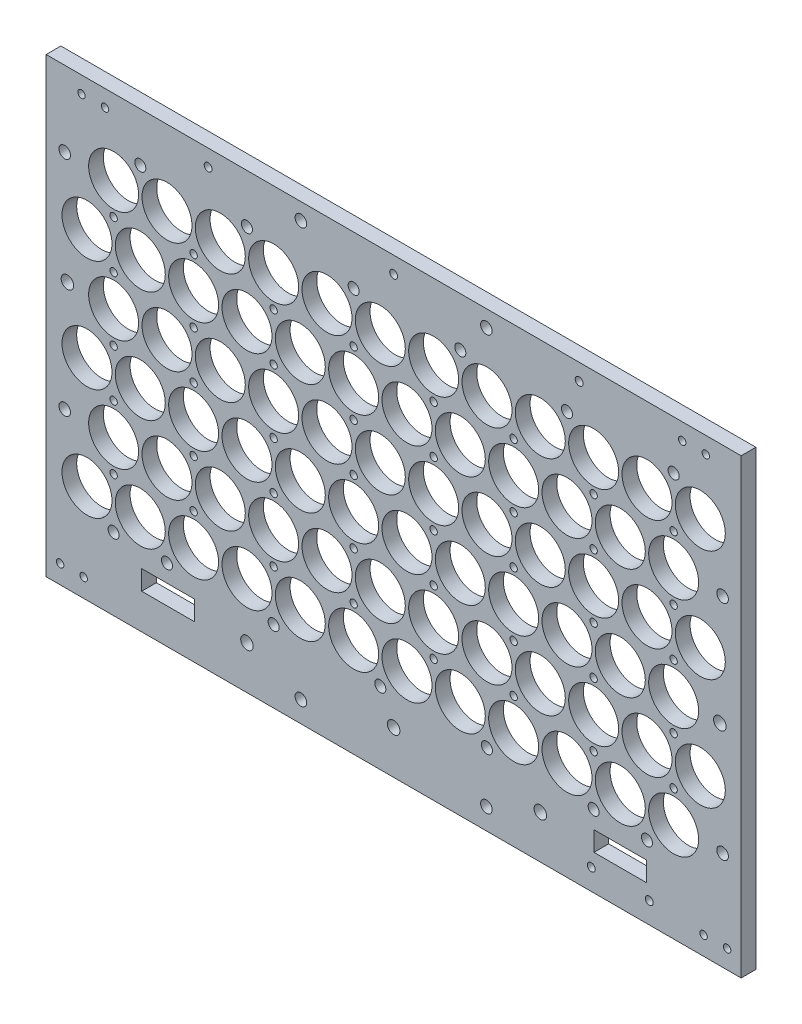
SolidWorks part; units mm, degrees
material "ABS"
ref_plane "X-Y Datum" through (0, 0, 0) normal (0, 0, 1) x (1, 0, 0)
ref_plane "X-Z Datum" through (0, 0, 0) normal (0, 1, 0) x (1, 0, 0)
ref_plane "Y-Z Datum" through (0, 0, 0) normal (1, 0, 0) x (0, 0, -1)
sketch "Sketch1" plane through (0, 0, 0) normal (0, 0, 1) x (1, 0, 0)
  line L1 (-143.025, 70.775) -> (143.025, 70.775)
  line L2 (-143.025, 70.775) -> (-143.025, -70.775)
  line L3 (-143.025, -70.775) -> (143.025, -70.775)
  line L4 (143.025, 70.775) -> (143.025, -70.775)
  line L5 (-143.025, 70.775) -> (143.025, -70.775) construction
  line L6 (-143.025, -70.775) -> (143.025, 70.775) construction
  line L13 (-149.85, -102.6) -> (149.85, -102.6)
  line L14 (-149.85, 91.65) -> (149.85, 91.65)
  line L15 (-149.85, 91.65) -> (-149.85, -102.6)
  line L16 (149.85, 91.65) -> (149.85, -102.6)
  line L17 (149.85, 70.775) -> (149.85, -70.775) construction
  line L18 (-143.025, 91.65) -> (143.025, 91.65) construction
  line L19 (-143.025, -102.6) -> (143.025, -102.6) construction
  line L20 (-149.85, 70.775) -> (-149.85, -70.775) construction
  line L21 (-132.25, -60) -> (-109.25, -60) construction
  circle A0 centre (-132.25, -60) radius 10.775
  circle A1 centre (-109.25, -60) radius 10.775 construction
  circle A2 centre (-120.75, -36) radius 10.775
  point P0 (0, 0)
  point P16 (-120.75, -60)
  dimension "D1" = 21.55
  dimension "D2" = 23
  dimension "D3" = 24
  dimension "D5" = 141.55
  dimension "D6" = 286.05
  dimension "D7" = 31.825
  dimension "D8" = 20.875
  dimension "D9" = 6.825
  dimension "D10" = 6.825
extrude "Boss-Extrude1" add sketch "Sketch1" along normal blind 6.35
sketch "Sketch3" plane through (0, 0, 6.35) normal (0, 0, 1) x (1, 0, 0)
  line L4 (143.025, 70.775) -> (-143.025, 70.775)
  line L5 (143.025, -70.775) -> (143.025, 70.775)
  line L6 (-143.025, -70.775) -> (143.025, -70.775)
  line L7 (-143.025, 70.775) -> (-143.025, -70.775)
  line L8 (143.025, 70.775) -> (-143.025, 70.775)
  line L9 (143.025, -70.775) -> (143.025, 70.775)
  line L10 (-143.025, -70.775) -> (143.025, -70.775)
  line L11 (-143.025, 70.775) -> (-143.025, -70.775)
  circle A1 centre (-120.75, -36) radius 10.775
  circle A2 centre (-120.75, -36) radius 10.775
  circle A3 centre (-132.25, -60) radius 10.775
  circle A4 centre (-132.25, -60) radius 10.775
  dimension "D1" = 0
  dimension "D2" = 0
  dimension "D3" = 0
extrude "Cut-Extrude1" cut sketch "Sketch3" against normal through all contours A4
sketch "Sketch4" plane through (0, 0, 6.35) normal (0, 0, 1) x (1, 0, 0)
  line L4 (143.025, 70.775) -> (-143.025, 70.775)
  line L5 (143.025, -70.775) -> (143.025, 70.775)
  line L6 (-143.025, -70.775) -> (143.025, -70.775)
  line L7 (-143.025, 70.775) -> (-143.025, -70.775)
  line L8 (143.025, 70.775) -> (-143.025, 70.775)
  line L9 (143.025, -70.775) -> (143.025, 70.775)
  line L10 (-143.025, -70.775) -> (143.025, -70.775)
  line L11 (-143.025, 70.775) -> (-143.025, -70.775)
  circle A1 centre (-120.75, -36) radius 10.775
  circle A2 centre (-120.75, -36) radius 10.775
  circle A3 centre (-132.25, -60) radius 10.775
  circle A4 centre (-132.25, -60) radius 10.775
  dimension "D1" = 0
  dimension "D2" = 0
  dimension "D3" = 0
extrude "Cut-Extrude2" cut sketch "Sketch4" against normal through all contours A2
pattern_linear "LPattern1" count 12 spacing 23 along (1, 0, 0) of "Cut-Extrude1", "Cut-Extrude2"
pattern_linear "LPattern2" count 3 spacing 48 along (0, 1, 0) of "LPattern1", "Cut-Extrude1", "Cut-Extrude2"
sketch "Sketch5" plane through (0, 0, 6.35) normal (0, 0, 1) x (1, 0, 0)
  line L4 (105.3154, -79.3475) -> (90.1846, -79.3475)
  line L5 (90.37, -80.3) -> (90.37, -83.4115)
  line L6 (90.37, -83.4115) -> (105.13, -83.4115)
  line L7 (105.13, -83.4115) -> (105.13, -80.3)
  line L8 (105.3154, -79.3475) -> (90.1846, -79.3475)
  line L9 (90.37, -80.3) -> (90.37, -83.4115)
  line L10 (90.37, -83.4115) -> (105.13, -83.4115)
  line L11 (105.13, -83.4115) -> (105.13, -80.3)
  line L12 (-108.668, -78.95) -> (-108.668, -87.4115)
  line L13 (-108.668, -87.4115) -> (-85.908, -87.4115)
  line L14 (-85.908, -87.4115) -> (-85.908, -78.95)
  line L15 (86.37, -78.95) -> (86.37, -87.4115)
  line L16 (-89.7226, -79.3475) -> (-104.8534, -79.3475)
  line L17 (-104.668, -80.3) -> (-104.668, -83.4115)
  line L18 (-104.668, -83.4115) -> (-89.908, -83.4115)
  line L19 (-89.908, -83.4115) -> (-89.908, -80.3)
  line L20 (-89.7226, -79.3475) -> (-104.8534, -79.3475)
  line L21 (-104.668, -80.3) -> (-104.668, -83.4115)
  line L22 (-104.668, -83.4115) -> (-89.908, -83.4115)
  line L23 (-89.908, -83.4115) -> (-89.908, -80.3)
  line L24 (86.37, -87.4115) -> (109.13, -87.4115)
  line L25 (109.13, -87.4115) -> (109.13, -78.95)
  line L26 (149.85, -78.95) -> (-149.85, -78.95) construction
  line L27 (149.85, -78.95) -> (-149.85, -78.95)
  line L28 (109.13, -87.4115) -> (109.13, -80.3) construction
  line L29 (86.37, -80.3) -> (86.37, -87.4115) construction
  line L30 (-85.908, -87.4115) -> (-85.908, -80.3) construction
  line L31 (-108.668, -80.3) -> (-108.668, -87.4115) construction
  arc A2 (90.37, -80.3) -> (90.1846, -79.3475) centre (87.83, -80.3) ccw
  arc A3 (105.3154, -79.3475) -> (105.13, -80.3) centre (107.67, -80.3) ccw
  arc A4 (90.37, -80.3) -> (90.1846, -79.3475) centre (87.83, -80.3) ccw
  arc A5 (105.3154, -79.3475) -> (105.13, -80.3) centre (107.67, -80.3) ccw
  arc A8 (-104.668, -80.3) -> (-104.8534, -79.3475) centre (-107.208, -80.3) ccw
  arc A9 (-89.7226, -79.3475) -> (-89.908, -80.3) centre (-87.368, -80.3) ccw
  arc A10 (-104.668, -80.3) -> (-104.8534, -79.3475) centre (-107.208, -80.3) ccw
  arc A11 (-89.7226, -79.3475) -> (-89.908, -80.3) centre (-87.368, -80.3) ccw
  dimension "D1" = 0
  dimension "D2" = 0
  dimension "D3" = 4
extrude "Cut-Extrude3" cut sketch "Sketch5" against normal through all contours L25 L27 L15 L24 L8 A5 L11 L10 L9 A4 | A5 L8 A4 L9 L10 L11 | L14 L27 L12 L13 L20 A11 L23 L22 L21 A10 | A11 L20 A10 L21 L22 L23
sketch "Sketch7" plane through (0, 0, 6.35) normal (0, 0, 1) x (1, 0, 0)
  point P0 (0, 85.3)
  point P1 (80, 85.3)
  point P3 (-124.45, 85.3)
  point P5 (-134.61, 85.3)
  point P7 (-133.6575, -94.6)
  point P9 (-143.8175, -94.6)
  point P11 (133.6575, -94.6)
  point P13 (143.8175, -94.6)
  point P17 (124.45, 85.3)
  point P19 (134.61, 85.3)
  point P21 (110.25, -93.5057)
  point P23 (85.25, -93.5057)
  point P28 (-80, 85.3)
hole_wizard "M3 Clearance Hole1" positions "Sketch8" profile "Sketch9" hole size "M3" standard "ANSI Metric" end condition through all
sketch "Sketch8" plane through (0, 0, 6.35) normal (0, 0, 1) x (1, 0, 0)
  point P3 (124.45, 85.3)
  point P6 (134.61, 85.3)
  point P12 (-124.45, 85.3)
  point P15 (-134.61, 85.3)
  point P18 (-143.8175, -94.6)
  point P21 (-133.6575, -94.6)
  point P24 (133.6575, -94.6)
  point P27 (143.8175, -94.6)
sketch "Sketch9" plane through (124.45, 85.3, 6.35) normal (1, 0, 0) x (0, -1, 0)
  line L0 (0, 0) -> (0, 6.35)
  line L1 (0, 6.35) -> (1.6, 6.35)
  line L2 (1.6, 6.35) -> (1.6, 0)
  line L5 (1.6, 0) -> (0, 0)
  line L11 (0, -6.35) -> (0, 107.95) construction
  dimension "Thru Hole Dia." = 3.2
  dimension "Thru Hole Depth" = 6.35
hole_wizard "M3 Clearance Hole2" positions "Sketch20" profile "Sketch13" hole size "M3" standard "ANSI Metric" end condition through all
sketch "Sketch20" plane through (0, 0, 6.35) normal (0, 0, 1) x (1, 0, 0)
  point P0 (110.25, -93.5057)
  point P3 (85.25, -93.5057)
  point P6 (-80, 85.3)
  point P9 (0, 85.3)
  point P12 (80, 85.3)
  point P23 (0, 0)
  point P24 (0, 0)
sketch "Sketch13" plane through (110.25, -93.5057, 6.35) normal (1, 0, 0) x (0, -1, 0)
  line L0 (0, 0) -> (0, 6.35)
  line L1 (0, 6.35) -> (1.7, 6.35)
  line L2 (1.7, 6.35) -> (1.7, 0)
  line L5 (1.7, 0) -> (0, 0)
  line L11 (0, -6.35) -> (0, 107.95) construction
  dimension "Thru Hole Dia." = 3.4
  dimension "Thru Hole Depth" = 6.35
sketch "Sketch14" plane through (0, 0, 6.35) normal (0, 0, 1) x (1, 0, 0)
  line L0 (131.525, -12) -> (149.85, -12) construction
  line L1 (149.85, 91.65) -> (149.85, -102.6) construction
  line L2 (-131.525, 12) -> (-149.85, 12) construction
  line L3 (-149.85, 91.65) -> (-149.85, -102.6) construction
  line L4 (149.85, -78.95) -> (-149.85, -78.95) construction
  line L5 (149.85, -78.95) -> (-149.85, -78.95) construction
  line L6 (149.85, -83.95) -> (-149.85, -83.95) construction
  line L7 (68.55, -70.9014) -> (57.95, -70.9014) construction
  line L8 (68.55, -67.0427) -> (68.55, -74.76) construction
  line L9 (57.95, -67.0427) -> (57.95, -74.76) construction
  line L10 (63.25, -70.9014) -> (63.25, -83.95) construction
  line L18 (0, -3.4925) -> (0, 3.4925) construction
  circle A0 centre (120.75, -12) radius 10.775 construction
  circle A1 centre (-120.75, 12) radius 10.775 construction
  circle A2 centre (140.6875, -12) radius 2.7
  circle A3 centre (-140.6875, 12) radius 2.7
  circle A4 centre (63.25, -83.95) radius 2.7
  circle A6 centre (-63.25, -83.95) radius 2.7
  circle A8 centre (0, -83.95) radius 2.7
  dimension "D1" = 5.4
  dimension "D3" = 5.4
  dimension "D2" = 5
extrude "Cut-Extrude4" cut sketch "Sketch14" against normal through all
sketch "Sketch15" plane through (0, 0, 6.35) normal (0, 0, 1) x (1, 0, 0)
  line L0 (-6.35, 85.3) -> (86.35, 85.3) construction
  line L1 (-6.35, 90.65) -> (-6.35, 79.95) construction
  line L2 (86.35, 79.95) -> (86.35, 90.65) construction
  line L3 (-86.35, 85.3) -> (6.35, 85.3) construction
  line L4 (-86.35, 90.65) -> (-86.35, 79.95) construction
  line L5 (6.35, 79.95) -> (6.35, 90.65) construction
  line L6 (131.525, 36) -> (149.85, 36) construction
  line L7 (149.85, 94.825) -> (149.85, -105.775) construction
  line L8 (131.525, -60) -> (149.85, -60) construction
  line L9 (-131.525, -36) -> (-149.85, -36) construction
  line L10 (-149.85, -105.775) -> (-149.85, 94.825) construction
  line L11 (-131.525, 60) -> (-149.85, 60) construction
  line L12 (-40, 85.3) -> (-40, -102.6) construction
  line L13 (-149.85, -102.6) -> (149.85, -102.6) construction
  line L14 (40, 85.3) -> (40, -102.6) construction
  line L16 (85.25, -93.5057) -> (-85.25, -93.5057) construction
  circle A0 centre (-40, 85.3) radius 2.5
  circle A1 centre (40, 85.3) radius 2.5
  circle A2 centre (120.75, 36) radius 10.775 construction
  circle A3 centre (120.75, -60) radius 10.775 construction
  circle A4 centre (141.85, 36) radius 2.5
  circle A5 centre (141.85, -60) radius 2.5
  circle A6 centre (-120.75, -36) radius 10.775 construction
  circle A7 centre (-120.75, 60) radius 10.775 construction
  circle A8 centre (-141.85, -36) radius 2.5
  circle A9 centre (-141.85, 60) radius 2.5
  circle A10 centre (-40, -93.5057) radius 2.5
  circle A11 centre (40, -93.5057) radius 2.5
  dimension "D1" = 5
  dimension "D2" = 8
  dimension "D3" = 8
  dimension "D4" = 8
  dimension "D5" = 8
extrude "Cut-Extrude5" cut sketch "Sketch15" against normal through all
sketch "Sketch16" plane through (0, 0, 6.35) normal (0, 0, 1) x (1, 0, 0)
  circle A0 centre (86.25, 46.29) radius 1.1906 construction
  circle A1 centre (120.75, 49.71) radius 1.1906 construction
  circle A2 centre (86.25, 25.71) radius 1.1906 construction
  circle A3 centre (120.75, 22.29) radius 1.1906 construction
  circle A4 centre (86.25, -1.71) radius 1.1906 construction
  circle A5 centre (120.75, 1.71) radius 1.1906 construction
  circle A6 centre (86.25, -22.29) radius 1.1906 construction
  circle A7 centre (120.75, -25.71) radius 1.1906 construction
  circle A8 centre (86.25, -49.71) radius 1.1906 construction
  circle A9 centre (120.75, -46.29) radius 1.1906 construction
  circle A10 centre (86.25, 46.29) radius 1.1906 construction
  circle A11 centre (120.75, 49.71) radius 1.1906 construction
  circle A12 centre (86.25, 25.71) radius 1.1906 construction
  circle A13 centre (120.75, 22.29) radius 1.1906 construction
  circle A14 centre (86.25, -1.71) radius 1.1906 construction
  circle A15 centre (120.75, 1.71) radius 1.1906 construction
  circle A16 centre (86.25, -22.29) radius 1.1906 construction
  circle A17 centre (120.75, -25.71) radius 1.1906 construction
  circle A18 centre (86.25, -49.71) radius 1.1906 construction
  circle A19 centre (120.75, -46.29) radius 1.1906 construction
  circle A20 centre (86.25, -49.71) radius 1.5875
  circle A21 centre (120.75, -46.29) radius 1.5875
  circle A22 centre (120.75, -25.71) radius 1.5875
  circle A23 centre (86.25, -22.29) radius 1.5875
  circle A24 centre (120.75, 1.71) radius 1.5875
  circle A25 centre (86.25, -1.71) radius 1.5875
  circle A26 centre (120.75, 22.29) radius 1.5875
  circle A27 centre (86.25, 25.71) radius 1.5875
  circle A28 centre (120.75, 49.71) radius 1.5875
  circle A29 centre (86.25, 46.29) radius 1.5875
  dimension "D1" = 3.175
extrude "Cut-Extrude6" cut sketch "Sketch16" against normal through all
pattern_linear "LPattern3" count 4 spacing 69 along (-1, 0, 0) of "Cut-Extrude6"
sketch "Sketch18" plane through (0, 0, 6.35) normal (0, 0, 1) x (1, 0, 0)
  circle A0 centre (-120.75, -71.41) radius 1.5875 construction
  circle A1 centre (-97.75, -71.41) radius 1.5875 construction
  circle A2 centre (-51.75, -71.41) radius 1.5875 construction
  circle A3 centre (-5.75, -71.41) radius 1.5875 construction
  circle A4 centre (40.25, -71.41) radius 1.5875 construction
  circle A5 centre (-109.25, 71.41) radius 1.5875 construction
  circle A6 centre (-63.25, 71.41) radius 1.5875 construction
  circle A7 centre (-17.25, 71.41) radius 1.5875 construction
  circle A8 centre (28.75, 71.41) radius 1.5875 construction
  circle A9 centre (74.75, 71.41) radius 1.5875 construction
  circle A10 centre (120.75, 71.41) radius 1.5875 construction
  circle A11 centre (86.25, -71.41) radius 1.5875 construction
  circle A12 centre (109.25, -71.41) radius 1.5875 construction
  circle A13 centre (-120.75, -71.41) radius 1.5875 construction
  circle A14 centre (-97.75, -71.41) radius 1.5875 construction
  circle A15 centre (-51.75, -71.41) radius 1.5875 construction
  circle A16 centre (-5.75, -71.41) radius 1.5875 construction
  circle A17 centre (40.25, -71.41) radius 1.5875 construction
  circle A18 centre (-109.25, 71.41) radius 1.5875 construction
  circle A19 centre (-63.25, 71.41) radius 1.5875 construction
  circle A20 centre (-17.25, 71.41) radius 1.5875 construction
  circle A21 centre (28.75, 71.41) radius 1.5875 construction
  circle A22 centre (74.75, 71.41) radius 1.5875 construction
  circle A23 centre (120.75, 71.41) radius 1.5875 construction
  circle A24 centre (86.25, -71.41) radius 1.5875 construction
  circle A25 centre (109.25, -71.41) radius 1.5875 construction
  circle A26 centre (109.25, -71.41) radius 2.3813
  circle A27 centre (86.25, -71.41) radius 2.3813
  circle A28 centre (120.75, 71.41) radius 2.3813
  circle A29 centre (74.75, 71.41) radius 2.3813
  circle A30 centre (28.75, 71.41) radius 2.3813
  circle A31 centre (-17.25, 71.41) radius 2.3812
  circle A32 centre (-63.25, 71.41) radius 2.3812
  circle A33 centre (-109.25, 71.41) radius 2.3813
  circle A34 centre (40.25, -71.41) radius 2.3812
  circle A35 centre (-5.75, -71.41) radius 2.3812
  circle A36 centre (-51.75, -71.41) radius 2.3812
  circle A37 centre (-97.75, -71.41) radius 2.3813
  circle A38 centre (-120.75, -71.41) radius 2.3813
  dimension "D1" = 4.7625
extrude "Cut-Extrude7" cut sketch "Sketch18" against normal through all
sketch "Sketch19" plane through (0, 91.65, 0) normal (0, 1, 0) x (1, 0, 0)
  line L4 (149.85, 0) -> (-149.85, 0)
  line L5 (-149.85, 0) -> (-149.85, -6.35)
  line L6 (-149.85, -6.35) -> (149.85, -6.35)
  line L7 (149.85, -6.35) -> (149.85, 0)
  line L8 (149.85, 0) -> (-149.85, 0)
  line L9 (-149.85, 0) -> (-149.85, -6.35)
  line L10 (-149.85, -6.35) -> (149.85, -6.35)
  line L11 (149.85, -6.35) -> (149.85, 0)
  dimension "D1" = 0
extrude "Boss-Extrude2" add sketch "Sketch19" along normal blind 0.7937
